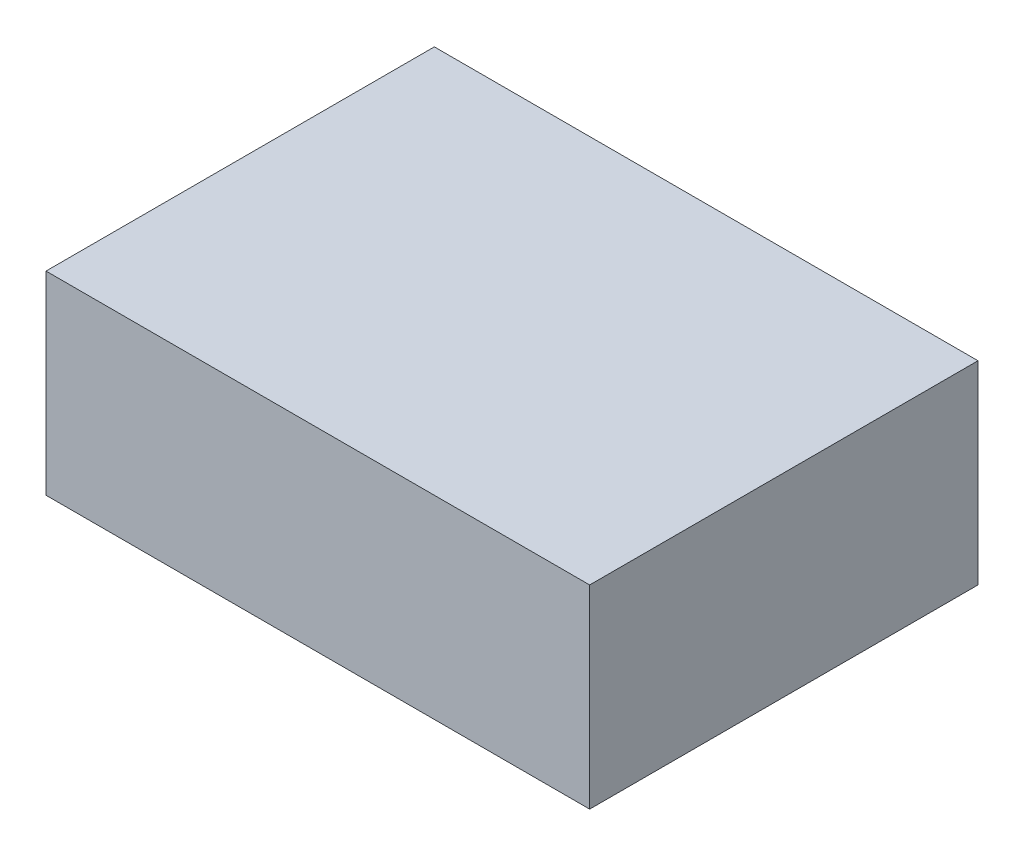
SolidWorks part; units mm, degrees
ref_plane "Спереди" through (0, 0, 0) normal (0, 0, 1) x (1, 0, 0)
ref_plane "Сверху" through (0, 0, 0) normal (0, 1, 0) x (1, 0, 0)
ref_plane "Справа" through (0, 0, 0) normal (1, 0, 0) x (0, 0, -1)
sketch "Эскиз1" plane through (0, 0, 0) normal (0, 1, 0) x (1, 0, 0)
  line L1 (0, 0) -> (5.6, 0)
  line L2 (0, 0) -> (0, 4)
  line L3 (0, 4) -> (5.6, 4)
  line L4 (5.6, 0) -> (5.6, 4)
  dimension "D1" = 4
  dimension "D2" = 5.6
extrude "Бобышка-Вытянуть1" add sketch "Эскиз1" along normal blind 2
